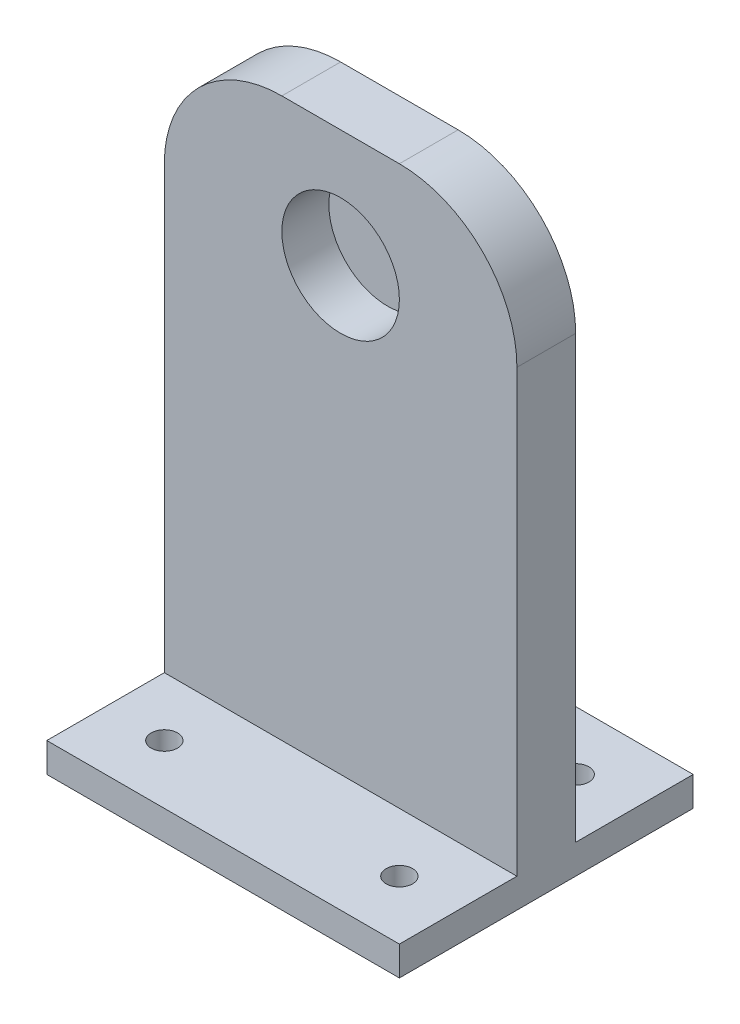
SolidWorks part; units mm, degrees
ref_plane "前视基准面" through (0, 0, 0) normal (0, 0, 1) x (1, 0, 0)
ref_plane "上视基准面" through (0, 0, 0) normal (0, 1, 0) x (1, 0, 0)
ref_plane "右视基准面" through (0, 0, 0) normal (1, 0, 0) x (0, 0, -1)
sketch "草图1" plane through (0, 0, 0) normal (0, 0, 1) x (1, 0, 0)
  line L0 (0, 100) -> (0, 0) construction
  line L2 (-30, 100) -> (30, 100)
  line L3 (-30, 100) -> (-30, 0)
  line L4 (-30, 0) -> (30, 0)
  line L5 (30, 100) -> (30, 0)
  circle A0 centre (0, 80) radius 10
  dimension "D4" = 20
  dimension "D1" = 100
  dimension "D2" = 60
  dimension "D3" = 30
  dimension "D5" = 80
  dimension "D6" = 100
extrude "凸台-拉伸1" add sketch "草图1" along normal blind 10
sketch "草图2" plane through (0, 0, 0) normal (0, 0, -1) x (-1, 0, 0)
  circle A0 centre (0, 80) radius 10
extrude "凸台-拉伸2" add sketch "草图2" against normal blind 2
fillet "圆角1" radius 20 2 edges at (30, 100, 5) (-30, 100, 5)
sketch "草图3" plane through (0, 0, 0) normal (0, -1, 0) x (1, 0, 0)
  line L0 (-40.659, 5) -> (46.5829, 5) construction
  line L5 (30, 10) -> (30, 0) construction
  line L6 (-30, 30) -> (30, 30)
  line L7 (-30, 30) -> (-30, -20)
  line L8 (-30, -20) -> (30, -20)
  line L9 (30, 30) -> (30, -20)
  line L10 (-30, 10) -> (-30, 0) construction
  dimension "D1" = 50
  dimension "D2" = 25
extrude "凸台-拉伸3" add sketch "草图3" against normal blind 5
sketch "草图4" plane through (0, 5, 0) normal (0, 1, 0) x (1, 0, 0)
  line L0 (0, 26.898) -> (0, -45.0743) construction
  line L1 (-30, 10) -> (30, 10) construction
  line L2 (-30, 0) -> (-30, 20) construction
  line L3 (30, 20) -> (30, 0) construction
  line L4 (30, -20) -> (-30, -20) construction
  line L5 (30, -10) -> (30, -30) construction
  line L6 (-30, -30) -> (-30, -10) construction
  circle A0 centre (-20, 10) radius 2.25
  circle A1 centre (20, 10) radius 2.25
  circle A2 centre (-20, -20) radius 2.25
  circle A3 centre (20, -20) radius 2.25
  dimension "D1" = 4.5
  dimension "D2" = 4.5
  dimension "D3" = 4.5
  dimension "D4" = 4.5
  dimension "D5" = 20
  dimension "D6" = 20
  dimension "D7" = 20
  dimension "D8" = 20
extrude "切除-拉伸1" cut sketch "草图4" against normal through all
